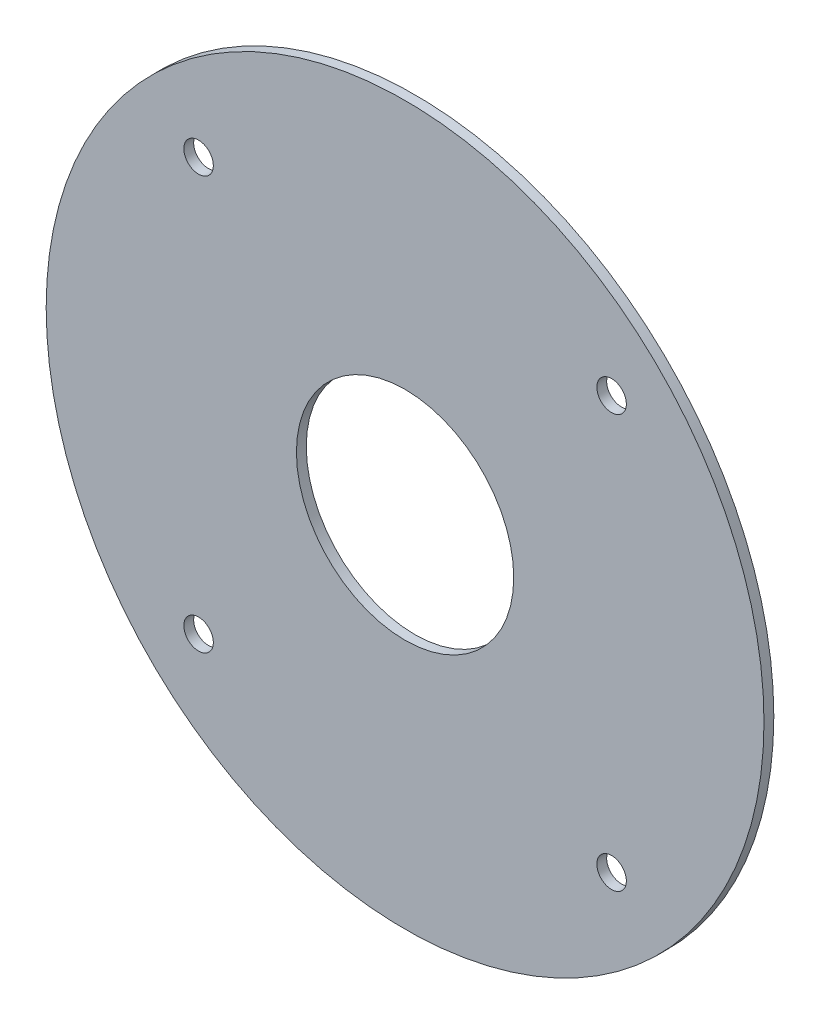
SolidWorks part; units mm, degrees
material "1060 合金"
ref_plane "前视基准面" through (0, 0, 0) normal (0, 0, 1) x (1, 0, 0)
ref_plane "上视基准面" through (0, 0, 0) normal (0, 1, 0) x (1, 0, 0)
ref_plane "右视基准面" through (0, 0, 0) normal (1, 0, 0) x (0, 0, -1)
other "Configuration Table"
sketch "草图1" plane through (0, 0, 0) normal (0, 0, 1) x (1, 0, 0)
  line L1 (-75.0787, -75.7648) -> (-117.0808, -75.7648) construction
  line L2 (-75.0787, -75.7648) -> (-75.0787, -33.7626) construction
  line L3 (-75.0787, -33.7626) -> (-117.0808, -33.7626) construction
  line L4 (-117.0808, -75.7648) -> (-117.0808, -33.7626) construction
  line L5 (-75.0787, -75.7648) -> (-117.0808, -33.7626) construction
  line L6 (-75.0787, -33.7626) -> (-117.0808, -75.7648) construction
  circle A0 centre (-96.0797, -54.7637) radius 11.05
  circle A1 centre (-96.0797, -54.7637) radius 36.5
  circle A2 centre (-96.0797, -54.7637) radius 29.7 construction
  circle A3 centre (-117.0808, -33.7626) radius 2.8 construction
  circle A4 centre (-96.0797, -54.7637) radius 32.5 construction
  circle A5 centre (-117.0808, -33.7626) radius 1.5
  circle A6 centre (-117.0808, -75.7648) radius 1.5
  circle A7 centre (-75.0787, -75.7648) radius 1.5
  circle A8 centre (-75.0787, -33.7626) radius 1.5
  dimension "D1" = 22.1
  dimension "D2" = 73
  dimension "D3" = 3
  dimension "D4" = 5.6
extrude "凸台-拉伸1" add sketch "草图1" along normal blind 1 contours A1 A0
